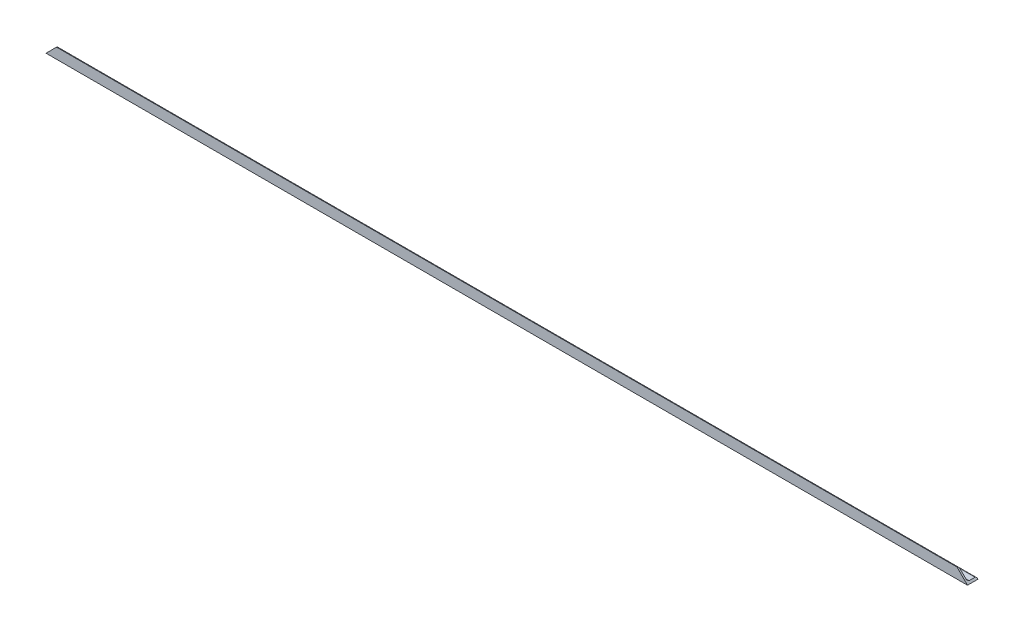
SolidWorks part; units mm, degrees
ref_plane "Front Plane" through (0, 0, 0) normal (0, 0, 1) x (1, 0, 0)
ref_plane "Top Plane" through (0, 0, 0) normal (0, 1, 0) x (1, 0, 0)
ref_plane "Right Plane" through (0, 0, 0) normal (1, 0, 0) x (0, 0, -1)
sketch "Sketch1" plane through (0, 0, 0) normal (0, 1, 0) x (1, 0, 0)
  line L0 (0, 0) -> (1754, 0)
  dimension "D1" = 1754
other "L angle (equal) 20X20X3(1)"
ref_plane "Plane1" through (0, 0, 0) normal (1, 0, 0) x (0, 0, -1)
sketch "Sketch16" plane through (0, 0, 0) normal (1, 0, 0) x (0, 0, -1)
  line L0 (0, 20) -> (0, 0)
  line L2 (3, 17) -> (3, 6.5)
  line L3 (6.5, 3) -> (17, 3)
  line L5 (20, 0) -> (0, 0)
  arc A0 (3, 17) -> (0, 20) centre (0, 17) ccw
  arc A1 (20, 0) -> (17, 3) centre (17, 0) ccw
  arc A2 (6.5, 3) -> (3, 6.5) centre (6.5, 6.5) cw
  point P8 (0, 10)
  point P9 (10, 0)
  point P10 (0, 0)
  dimension "Radius_2" = 3
  dimension "Radius_1" = 3.5
  dimension "V_leg" = 20
  dimension "H_leg" = 20
  dimension "thickness" = 3
sketch "Sketch14" plane through (0, 0, 0) normal (0, 0, 1) x (1, 0, 0)
  line L0 (1754, 0) -> (1754, 20)
  line L1 (0, 20) -> (0, 0)
  line L2 (20, 20) -> (0, 0)
  line L3 (1734, 20) -> (1754, 0)
  line L4 (0, 20) -> (0, 0)
  line L5 (0, 0) -> (1754, 0)
  line L6 (1754, 0) -> (1754, 20)
  line L7 (1754, 20) -> (0, 20)
  line L8 (0, 20) -> (0, 0) construction
  line L10 (1754, 0) -> (1754, 20) construction
  line L11 (1754, 20) -> (1734, 20)
  line L12 (20, 20) -> (0, 20)
  dimension "D2" = 20
  dimension "D3" = 20
  dimension "D1" = 0
extrude "Cut-Extrude1" cut sketch "Sketch14" against normal through all
